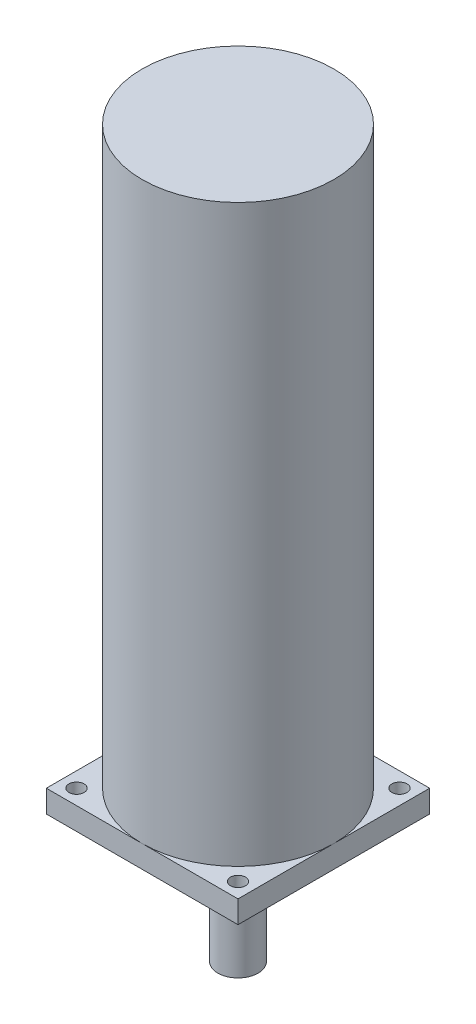
SolidWorks part; units mm, degrees
ref_plane "Front Plane" through (0, 0, 0) normal (0, 0, 1) x (1, 0, 0)
ref_plane "Top Plane" through (0, 0, 0) normal (0, 1, 0) x (1, 0, 0)
ref_plane "Right Plane" through (0, 0, 0) normal (1, 0, 0) x (0, 0, -1)
sketch "Sketch1" plane through (0, 0, 0) normal (0, 1, 0) x (1, 0, 0)
  line L0 (0, 0) -> (0, 36.5325) construction
  line L5 (-19.05, -19.05) -> (19.05, -19.05)
  line L6 (-19.05, -19.05) -> (-19.05, 19.05)
  line L7 (-19.05, 19.05) -> (19.05, 19.05)
  line L8 (19.05, -19.05) -> (19.05, 19.05)
  line L9 (-19.05, -19.05) -> (19.05, 19.05) construction
  line L10 (-19.05, 19.05) -> (19.05, -19.05) construction
  line L11 (0, 0) -> (-43.2471, 0) construction
  circle A0 centre (-16.05, 16.05) radius 1.5
  circle A1 centre (16.05, 16.05) radius 1.5
  circle A2 centre (16.05, -16.05) radius 1.5
  circle A3 centre (-16.05, -16.05) radius 1.5
  point P0 (0, 0)
  dimension "D4" = 3
  dimension "D1" = 38.1
  dimension "D2" = 38.1
  dimension "D3" = 3
extrude "Boss-Extrude1" add sketch "Sketch1" along normal blind 4.445
sketch "Sketch2" plane through (0, 4.445, 0) normal (0, 1, 0) x (1, 0, 0)
  circle A0 centre (0, 0) radius 19.05
extrude "Boss-Extrude2" add sketch "Sketch2" along normal blind 114.3
sketch "Sketch3" plane through (0, 0, 0) normal (0, -1, 0) x (1, 0, 0)
  circle A0 centre (0, 0) radius 4
  dimension "D1" = 8
extrude "Boss-Extrude3" add sketch "Sketch3" along normal blind 25.4
